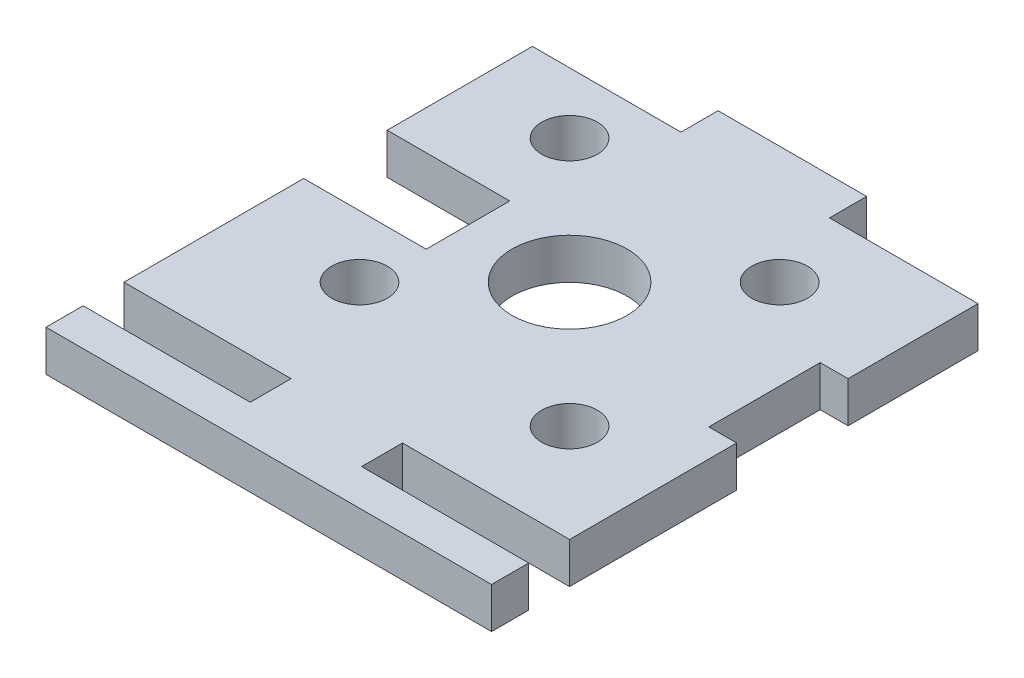
SolidWorks part; units mm, degrees
material "cardboard"
ref_plane "Front Plane" through (0, 0, 0) normal (0, 0, 1) x (1, 0, 0)
ref_plane "Top Plane" through (0, 0, 0) normal (0, 1, 0) x (1, 0, 0)
ref_plane "Right Plane" through (0, 0, 0) normal (1, 0, 0) x (0, 0, -1)
sketch "Sketch1" plane through (0, 0, 0) normal (0, 1, 0) x (1, 0, 0)
  line L0 (78.5546, 12.1341) -> (71.7044, 8.1792)
  line L1 (104.0546, -11.8659) -> (110.9047, -7.911)
  line L2 (119.2044, 8.1792) -> (110.9047, 8.1792)
  line L3 (119.2044, -7.911) -> (110.9047, -7.911)
  line L4 (71.7044, 8.1792) -> (63.4047, 8.1792)
  line L5 (126.0546, 12.1341) -> (119.2044, 8.1792)
  line L6 (126.0546, -11.8659) -> (119.2044, -7.911)
  line L7 (104.0546, 12.1341) -> (110.9047, 8.1792)
  line L8 (126.0546, 12.1341) -> (138.8046, 12.1341)
  line L9 (126.0546, -11.8659) -> (162.8046, -11.8659)
  line L10 (56.5546, 12.1341) -> (63.4047, 8.1792)
  line L11 (56.5546, -11.8659) -> (63.4047, -7.911)
  line L12 (78.5546, -11.8659) -> (71.7044, -7.911)
  line L13 (71.7044, -7.911) -> (63.4047, -7.911)
  line L14 (78.5546, 12.1341) -> (104.0546, 12.1341)
  line L15 (78.5546, -11.8659) -> (104.0546, -11.8659)
  line L16 (-11.1954, 77.8841) -> (-7.2405, 71.034)
  line L17 (12.8046, 103.3841) -> (8.8496, 110.2342)
  line L18 (-7.2405, 118.534) -> (-7.2405, 110.2342)
  line L19 (8.8496, 118.534) -> (8.8496, 110.2342)
  line L20 (-7.2405, 71.034) -> (-7.2405, 62.7342)
  line L21 (-11.1954, 125.3841) -> (-7.2405, 118.534)
  line L22 (12.8046, 125.3841) -> (8.8496, 118.534)
  line L23 (-11.1954, 103.3841) -> (-7.2405, 110.2342)
  line L24 (-11.1954, 125.3841) -> (-11.1954, 138.1341)
  line L25 (12.8046, 125.3841) -> (12.8046, 162.1341)
  line L26 (-11.1954, 55.8841) -> (-7.2405, 62.7342)
  line L27 (12.8046, 55.8841) -> (8.8496, 62.7342)
  line L28 (12.8046, 77.8841) -> (8.8496, 71.034)
  line L29 (8.8496, 71.034) -> (8.8496, 62.7342)
  line L30 (-11.1954, 77.8841) -> (-11.1954, 103.3841)
  line L31 (12.8046, 77.8841) -> (12.8046, 103.3841)
  line L32 (91.3046, 37.1341) -> (91.3046, 17.1341)
  line L33 (90.3046, 37.1341) -> (90.3046, 31.1341)
  line L34 (37.8046, 12.1341) -> (43.8046, 12.1341)
  line L35 (90.3046, 31.1341) -> (92.3046, 31.1341)
  line L36 (42.5546, 12.1341) -> (42.5546, 10.1341)
  line L37 (43.8046, 12.1341) -> (56.5546, 12.1341)
  line L38 (138.8046, 12.1341) -> (138.8046, -11.8659)
  line L39 (138.8046, 12.1341) -> (162.8046, 12.1341)
  line L40 (162.8046, 12.1341) -> (162.8046, 10.1341)
  line L41 (-27.6918, 14.4884) -> (0.8046, -14.008)
  line L42 (-27.6918, 14.4884) -> (-13.5497, 28.6305)
  line L43 (0.8046, -14.008) -> (14.9467, 0.1341)
  line L44 (-13.5497, 28.6305) -> (14.9467, 0.1341)
  line L45 (138.8046, 12.1341) -> (138.8046, 37.1341)
  line L46 (40.8046, 37.1341) -> (162.8046, 37.1341)
  line L47 (162.8046, 37.1341) -> (162.8046, 12.1341)
  line L48 (92.3046, 31.1341) -> (92.3046, 23.1341)
  line L49 (138.8046, 37.1341) -> (138.8046, 61.1341)
  line L50 (138.8046, 61.1341) -> (147.8046, 61.1341)
  line L51 (43.8046, 37.1341) -> (43.8046, 17.1341)
  line L52 (162.8046, 61.1341) -> (162.8046, 51.4561)
  line L53 (147.8046, 61.1341) -> (147.8046, 63.3341)
  line L54 (153.8046, 63.3341) -> (153.8046, 61.1341)
  line L55 (153.8046, 61.1341) -> (162.8046, 61.1341)
  line L56 (-58.1954, 138.1341) -> (-58.1954, 113.6341)
  line L57 (-38.1954, 113.6341) -> (-38.1954, 138.1341)
  line L58 (92.3046, 23.1341) -> (90.3046, 23.1341)
  line L59 (138.8046, -11.8659) -> (138.8046, -36.8659)
  line L60 (147.8046, -36.8659) -> (153.8046, -36.8659)
  line L61 (162.8046, -36.8659) -> (162.8046, -11.8659)
  line L62 (43.8046, -36.8659) -> (43.8046, -16.8659)
  line L63 (138.8046, -36.8659) -> (138.8046, -38.0459)
  line L64 (153.8046, -38.0459) -> (162.8046, -38.0459)
  line L65 (162.8046, -38.0459) -> (162.8046, -36.8659)
  line L66 (147.8046, -38.0459) -> (147.8046, -36.8659)
  line L67 (153.8046, -38.0459) -> (153.8046, -36.8659)
  line L68 (-37.3754, -137.8659) -> (-37.3754, -146.8659)
  line L69 (90.3046, 23.1341) -> (90.3046, 17.1341)
  line L70 (90.3046, 12.1341) -> (90.3046, 4.1341)
  line L71 (43.8046, -11.8659) -> (56.5546, -11.8659)
  line L72 (37.8046, -11.8659) -> (43.8046, -11.8659)
  line L73 (91.2784, 12.1341) -> (91.2784, -11.8659)
  line L74 (90.3046, 4.1341) -> (92.3046, 4.1341)
  line L75 (92.3046, 4.1341) -> (92.3046, -3.8659)
  line L76 (92.3046, -3.8659) -> (90.3046, -3.8659)
  line L77 (136.8046, 12.1341) -> (136.8046, 4.1341)
  line L78 (136.8046, 4.1341) -> (140.8046, 4.1341)
  line L79 (38.9846, 162.1341) -> (38.9846, 153.1341)
  line L80 (38.8046, 35.1341) -> (38.8046, 19.1341)
  line L81 (40.8046, 17.1341) -> (138.8046, 17.1341)
  line L82 (42.5546, 24.1341) -> (42.5546, 17.1341)
  line L83 (43.8046, 30.1341) -> (40.8046, 30.1341)
  line L84 (40.8046, 30.1341) -> (40.8046, 24.1341)
  line L85 (45.0546, 6.1341) -> (42.5546, 6.1341)
  line L86 (6.8046, -41.6159) -> (6.8046, -39.6159)
  line L87 (42.5546, -5.8659) -> (45.0546, -5.8659)
  line L88 (45.0546, 6.1341) -> (45.0546, -5.8659)
  line L89 (43.8046, 12.1341) -> (43.8046, 6.1341)
  line L90 (42.5546, 10.1341) -> (45.0546, 10.1341)
  line L91 (45.0546, 10.1341) -> (45.0546, 8.1341)
  line L92 (45.0546, 8.1341) -> (42.5546, 8.1341)
  line L93 (42.5546, 8.1341) -> (42.5546, 6.1341)
  line L94 (42.5546, -7.8659) -> (42.5546, -5.8659)
  line L95 (45.0546, -7.8659) -> (42.5546, -7.8659)
  line L96 (45.0546, -9.8659) -> (45.0546, -7.8659)
  line L97 (42.5546, -9.8659) -> (45.0546, -9.8659)
  line L98 (42.5546, -11.8659) -> (42.5546, -9.8659)
  line L99 (140.8046, 4.1341) -> (140.8046, -3.8659)
  line L100 (140.8046, -3.8659) -> (136.8046, -3.8659)
  line L101 (136.8046, -3.8659) -> (136.8046, -11.8659)
  line L102 (138.8046, 14.1341) -> (146.8046, 14.1341)
  line L103 (146.8046, 14.1341) -> (146.8046, 10.1341)
  line L104 (146.8046, 10.1341) -> (154.8046, 10.1341)
  line L105 (154.8046, 10.1341) -> (154.8046, 14.1341)
  line L106 (154.8046, 14.1341) -> (162.8046, 14.1341)
  line L107 (137.3046, 37.1341) -> (137.3046, 31.1341)
  line L108 (137.3046, 31.1341) -> (140.3046, 31.1341)
  line L109 (140.3046, 31.1341) -> (140.3046, 23.1341)
  line L110 (140.3046, 23.1341) -> (137.3046, 23.1341)
  line L111 (137.3046, 23.1341) -> (137.3046, 17.1341)
  line L112 (90.3046, -3.8659) -> (90.3046, -11.8659)
  line L113 (90.3046, -22.8659) -> (90.3046, -16.8659)
  line L114 (91.3046, -36.8659) -> (91.3046, -16.8659)
  line L115 (92.3046, -22.8659) -> (90.3046, -22.8659)
  line L116 (92.3046, -30.8659) -> (92.3046, -22.8659)
  line L117 (154.8046, -13.8659) -> (162.8046, -13.8659)
  line L118 (154.8046, -9.8659) -> (154.8046, -13.8659)
  line L119 (146.8046, -9.8659) -> (154.8046, -9.8659)
  line L120 (146.8046, -13.8659) -> (146.8046, -9.8659)
  line L121 (138.8046, -13.8659) -> (146.8046, -13.8659)
  line L122 (137.3046, -22.8659) -> (137.3046, -16.8659)
  line L123 (140.3046, -22.8659) -> (137.3046, -22.8659)
  line L124 (42.5546, 37.1341) -> (42.5546, 30.1341)
  line L125 (43.8046, 24.1341) -> (40.8046, 24.1341)
  line L126 (138.8046, -36.8659) -> (40.8046, -36.8659)
  line L127 (38.8046, -34.8659) -> (38.8046, -18.8659)
  line L128 (40.8046, -16.8659) -> (138.8046, -16.8659)
  line L129 (140.3046, -30.8659) -> (140.3046, -22.8659)
  line L130 (137.3046, -30.8659) -> (140.3046, -30.8659)
  line L131 (137.3046, -36.8659) -> (137.3046, -30.8659)
  line L132 (90.3046, -30.8659) -> (92.3046, -30.8659)
  line L133 (90.3046, -36.8659) -> (90.3046, -30.8659)
  line L134 (138.8046, 39.1341) -> (146.8046, 39.1341)
  line L135 (146.8046, 39.1341) -> (146.8046, 35.1341)
  line L136 (146.8046, 35.1341) -> (154.8046, 35.1341)
  line L137 (154.8046, 35.1341) -> (154.8046, 39.1341)
  line L138 (154.8046, 39.1341) -> (162.8046, 39.1341)
  line L139 (-43.6954, 133.8841) -> (-43.6954, 117.8841)
  line L140 (-55.1954, 133.8841) -> (-52.6954, 133.8841)
  line L141 (-55.1954, 133.8841) -> (-55.1954, 117.8841)
  line L142 (-55.1954, 117.8841) -> (-52.6954, 117.8841)
  line L143 (-52.6954, 133.8841) -> (-52.6954, 117.8841)
  line L144 (42.5546, -23.8659) -> (42.5546, -16.8659)
  line L145 (43.8046, -23.8659) -> (40.8046, -23.8659)
  line L146 (40.8046, -29.8659) -> (40.8046, -23.8659)
  line L147 (43.8046, -29.8659) -> (40.8046, -29.8659)
  line L148 (42.5546, -36.8659) -> (42.5546, -29.8659)
  line L149 (197.8046, 5.1341) -> (197.8046, -4.8659)
  line L150 (192.8046, 10.1341) -> (162.8046, 10.1341)
  line L151 (192.8046, -9.8659) -> (162.8046, -9.8659)
  line L152 (192.8046, 10.1341) -> (197.8046, 5.1341)
  line L153 (197.8046, -4.8659) -> (192.8046, -9.8659)
  line L154 (162.8046, -9.8659) -> (162.8046, -11.8659)
  line L155 (138.8046, 63.3341) -> (147.8046, 63.3341)
  line L156 (138.8046, 63.3341) -> (138.8046, 65.3341)
  line L157 (138.8046, 65.3341) -> (162.8046, 65.3341)
  line L158 (162.8046, 65.3341) -> (162.8046, 63.3341)
  line L159 (153.8046, 63.3341) -> (162.8046, 63.3341)
  line L160 (-41.1954, 117.8841) -> (-43.6954, 117.8841)
  line L161 (-41.1954, 133.8841) -> (-41.1954, 117.8841)
  line L162 (-41.1954, 133.8841) -> (-43.6954, 133.8841)
  line L163 (156.2046, 51.4561) -> (162.8046, 51.4561)
  line L164 (156.2046, 51.4561) -> (156.2046, 46.9561)
  line L165 (156.2046, 46.9561) -> (162.8046, 46.9561)
  line L166 (162.8046, 46.9561) -> (162.8046, 37.1341)
  line L167 (12.8046, -77.6159) -> (8.8496, -70.7658)
  line L168 (-11.1954, -103.1159) -> (-7.2405, -109.966)
  line L169 (8.8496, -118.2658) -> (8.8496, -109.966)
  line L170 (12.8046, -36.8659) -> (12.8046, -42.8659)
  line L171 (12.8046, -41.6159) -> (10.8046, -41.6159)
  line L172 (12.8046, -42.8659) -> (12.8046, -55.6159)
  line L173 (-7.2405, -118.2658) -> (-7.2405, -109.966)
  line L174 (8.8496, -70.7658) -> (8.8496, -62.466)
  line L175 (12.8046, -125.1159) -> (8.8496, -118.2658)
  line L176 (-11.1954, -125.1159) -> (-7.2405, -118.2658)
  line L177 (12.8046, -103.1159) -> (8.8496, -109.966)
  line L178 (12.8046, -125.1159) -> (12.8046, -137.8659)
  line L179 (-11.1954, -125.1159) -> (-11.1954, -161.8659)
  line L180 (12.8046, -55.6159) -> (8.8496, -62.466)
  line L181 (-11.1954, -55.6159) -> (-7.2405, -62.466)
  line L182 (37.8046, -42.8659) -> (17.8046, -42.8659)
  line L183 (-11.1954, -77.6159) -> (-7.2405, -70.7658)
  line L184 (-7.2405, -70.7658) -> (-7.2405, -62.466)
  line L185 (12.8046, -77.6159) -> (12.8046, -103.1159)
  line L186 (-11.1954, -77.6159) -> (-11.1954, -103.1159)
  line L187 (37.8046, -90.3659) -> (17.8046, -90.3659)
  line L188 (37.8046, -89.3659) -> (31.8046, -89.3659)
  line L189 (31.8046, -89.3659) -> (31.8046, -91.3659)
  line L190 (12.8046, -137.8659) -> (-11.1954, -137.8659)
  line L191 (12.8046, -137.8659) -> (12.8046, -161.8659)
  line L192 (12.8046, -161.8659) -> (10.8046, -161.8659)
  line L193 (12.8046, -137.8659) -> (37.8046, -137.8659)
  line L194 (37.8046, -39.8659) -> (37.8046, -161.8659)
  line L195 (-36.1954, -42.8659) -> (-16.1954, -42.8659)
  line L196 (37.8046, -161.8659) -> (12.8046, -161.8659)
  line L197 (31.8046, -91.3659) -> (23.8046, -91.3659)
  line L198 (37.8046, -137.8659) -> (61.8046, -137.8659)
  line L199 (61.8046, -137.8659) -> (61.8046, -146.8659)
  line L200 (61.8046, -161.8659) -> (52.1265, -161.8659)
  line L201 (61.8046, -146.8659) -> (64.0046, -146.8659)
  line L202 (64.0046, -152.8659) -> (61.8046, -152.8659)
  line L203 (61.8046, -152.8659) -> (61.8046, -161.8659)
  line L204 (-11.1954, -42.8659) -> (-11.1954, -55.6159)
  line L205 (-11.1954, -36.8659) -> (-11.1954, -42.8659)
  line L206 (23.8046, -91.3659) -> (23.8046, -89.3659)
  line L207 (-11.1954, -137.8659) -> (-36.1954, -137.8659)
  line L208 (-36.1954, -146.8659) -> (-36.1954, -152.8659)
  line L209 (38.9846, 147.1341) -> (38.9846, 138.1341)
  line L210 (35.8046, -37.8659) -> (19.8046, -37.8659)
  line L211 (17.8046, -39.8659) -> (17.8046, -137.8659)
  line L212 (24.8046, -41.6159) -> (17.8046, -41.6159)
  line L213 (30.8046, -42.8659) -> (30.8046, -39.8659)
  line L214 (30.8046, -39.8659) -> (24.8046, -39.8659)
  line L215 (6.8046, -44.1159) -> (6.8046, -41.6159)
  line L216 (-36.1954, -161.8659) -> (-11.1954, -161.8659)
  line L217 (-5.1954, -41.6159) -> (-5.1954, -44.1159)
  line L218 (6.8046, -44.1159) -> (-5.1954, -44.1159)
  line L219 (12.8046, -42.8659) -> (6.8046, -42.8659)
  line L220 (10.8046, -41.6159) -> (10.8046, -44.1159)
  line L221 (10.8046, -44.1159) -> (8.8046, -44.1159)
  line L222 (8.8046, -44.1159) -> (8.8046, -41.6159)
  line L223 (8.8046, -41.6159) -> (6.8046, -41.6159)
  line L224 (-7.1954, -41.6159) -> (-5.1954, -41.6159)
  line L225 (-7.1954, -44.1159) -> (-7.1954, -41.6159)
  line L226 (-9.1954, -44.1159) -> (-7.1954, -44.1159)
  line L227 (-9.1954, -41.6159) -> (-9.1954, -44.1159)
  line L228 (-11.1954, -41.6159) -> (-9.1954, -41.6159)
  line L229 (-36.1954, -137.8659) -> (-37.3754, -137.8659)
  line L230 (-37.3754, -152.8659) -> (-37.3754, -161.8659)
  line L231 (-37.3754, -161.8659) -> (-36.1954, -161.8659)
  line L232 (-37.3754, -146.8659) -> (-36.1954, -146.8659)
  line L233 (-37.3754, -152.8659) -> (-36.1954, -152.8659)
  line L234 (-161.1954, 38.3141) -> (-152.1954, 38.3141)
  line L235 (23.8046, -89.3659) -> (17.8046, -89.3659)
  line L236 (12.8046, -89.3659) -> (4.8046, -89.3659)
  line L237 (12.8046, -90.3397) -> (-11.1954, -90.3397)
  line L238 (4.8046, -89.3659) -> (4.8046, -91.3659)
  line L239 (4.8046, -91.3659) -> (-3.1954, -91.3659)
  line L240 (-3.1954, -91.3659) -> (-3.1954, -89.3659)
  line L241 (12.8046, -135.8659) -> (4.8046, -135.8659)
  line L242 (4.8046, -135.8659) -> (4.8046, -139.8659)
  line L243 (4.8046, -139.8659) -> (-3.1954, -139.8659)
  line L244 (-3.1954, -139.8659) -> (-3.1954, -135.8659)
  line L245 (-3.1954, -135.8659) -> (-11.1954, -135.8659)
  line L246 (14.8046, -137.8659) -> (14.8046, -145.8659)
  line L247 (14.8046, -145.8659) -> (10.8046, -145.8659)
  line L248 (10.8046, -145.8659) -> (10.8046, -153.8659)
  line L249 (10.8046, -153.8659) -> (14.8046, -153.8659)
  line L250 (14.8046, -153.8659) -> (14.8046, -161.8659)
  line L251 (37.8046, -136.3659) -> (31.8046, -136.3659)
  line L252 (31.8046, -136.3659) -> (31.8046, -139.3659)
  line L253 (31.8046, -139.3659) -> (23.8046, -139.3659)
  line L254 (37.8046, -41.6159) -> (30.8046, -41.6159)
  line L255 (24.8046, -42.8659) -> (24.8046, -39.8659)
  line L256 (-36.1954, -137.8659) -> (-36.1954, -39.8659)
  line L257 (-34.1954, -37.8659) -> (-18.1954, -37.8659)
  line L258 (-16.1954, -39.8659) -> (-16.1954, -137.8659)
  line L259 (23.8046, -139.3659) -> (23.8046, -136.3659)
  line L260 (23.8046, -136.3659) -> (17.8046, -136.3659)
  line L261 (-3.1954, -89.3659) -> (-11.1954, -89.3659)
  line L262 (-22.1954, -89.3659) -> (-16.1954, -89.3659)
  line L263 (-36.1954, -90.3659) -> (-16.1954, -90.3659)
  line L264 (-22.1954, -91.3659) -> (-22.1954, -89.3659)
  line L265 (-30.1954, -91.3659) -> (-22.1954, -91.3659)
  line L266 (-13.1954, -153.8659) -> (-13.1954, -161.8659)
  line L267 (-9.1954, -153.8659) -> (-13.1954, -153.8659)
  line L268 (-9.1954, -145.8659) -> (-9.1954, -153.8659)
  line L269 (-13.1954, -145.8659) -> (-9.1954, -145.8659)
  line L270 (-13.1954, -137.8659) -> (-13.1954, -145.8659)
  line L271 (-22.1954, -136.3659) -> (-16.1954, -136.3659)
  line L272 (-22.1954, -139.3659) -> (-22.1954, -136.3659)
  line L273 (-30.1954, -139.3659) -> (-22.1954, -139.3659)
  line L274 (-23.1954, -41.6159) -> (-16.1954, -41.6159)
  line L275 (-23.1954, -42.8659) -> (-23.1954, -39.8659)
  line L276 (-29.1954, -39.8659) -> (-23.1954, -39.8659)
  line L277 (-29.1954, -42.8659) -> (-29.1954, -39.8659)
  line L278 (-36.1954, -41.6159) -> (-29.1954, -41.6159)
  line L279 (-30.1954, -136.3659) -> (-30.1954, -139.3659)
  line L280 (-36.1954, -136.3659) -> (-30.1954, -136.3659)
  line L281 (-30.1954, -89.3659) -> (-30.1954, -91.3659)
  line L282 (-36.1954, -89.3659) -> (-30.1954, -89.3659)
  line L283 (39.8046, -137.8659) -> (39.8046, -145.8659)
  line L284 (39.8046, -145.8659) -> (35.8046, -145.8659)
  line L285 (35.8046, -145.8659) -> (35.8046, -153.8659)
  line L286 (35.8046, -153.8659) -> (39.8046, -153.8659)
  line L287 (39.8046, -153.8659) -> (39.8046, -161.8659)
  line L288 (5.8046, -196.8659) -> (-4.1954, -196.8659)
  line L289 (10.8046, -191.8659) -> (10.8046, -161.8659)
  line L290 (-9.1954, -191.8659) -> (-9.1954, -161.8659)
  line L291 (10.8046, -191.8659) -> (5.8046, -196.8659)
  line L292 (-4.1954, -196.8659) -> (-9.1954, -191.8659)
  line L293 (-9.1954, -161.8659) -> (-11.1954, -161.8659)
  line L294 (64.0046, -137.8659) -> (64.0046, -146.8659)
  line L295 (64.0046, -137.8659) -> (66.0046, -137.8659)
  line L296 (66.0046, -137.8659) -> (66.0046, -161.8659)
  line L297 (66.0046, -161.8659) -> (64.0046, -161.8659)
  line L298 (64.0046, -152.8659) -> (64.0046, -161.8659)
  line L299 (-36.1954, -11.8659) -> (-42.1954, -11.8659)
  line L300 (-40.9454, -11.8659) -> (-40.9454, -9.8659)
  line L301 (-42.1954, -11.8659) -> (-54.9454, -11.8659)
  line L302 (52.1265, -155.2659) -> (52.1265, -161.8659)
  line L303 (52.1265, -155.2659) -> (47.6265, -155.2659)
  line L304 (-42.1954, -36.8659) -> (-42.1954, -16.8659)
  line L305 (47.6265, -155.2659) -> (47.6265, -161.8659)
  line L306 (47.6265, -161.8659) -> (37.8046, -161.8659)
  line L307 (-76.9454, -11.8659) -> (-70.0953, -7.911)
  line L308 (-102.4454, 12.1341) -> (-109.2956, 8.1792)
  line L309 (-117.5953, -7.911) -> (-109.2956, -7.911)
  line L310 (-117.5953, 8.1792) -> (-109.2956, 8.1792)
  line L311 (-70.0953, -7.911) -> (-61.7956, -7.911)
  line L312 (-124.4454, -11.8659) -> (-117.5953, -7.911)
  line L313 (-124.4454, 12.1341) -> (-117.5953, 8.1792)
  line L314 (-102.4454, -11.8659) -> (-109.2956, -7.911)
  line L315 (-124.4454, -11.8659) -> (-137.1954, -11.8659)
  line L316 (-42.1954, 37.1341) -> (-42.1954, 17.1341)
  line L317 (-124.4454, 12.1341) -> (-161.1954, 12.1341)
  line L318 (-54.9454, -11.8659) -> (-61.7956, -7.911)
  line L319 (-54.9454, 12.1341) -> (-61.7956, 8.1792)
  line L320 (-76.9454, 12.1341) -> (-70.0953, 8.1792)
  line L321 (-70.0953, 8.1792) -> (-61.7956, 8.1792)
  line L322 (-76.9454, -11.8659) -> (-102.4454, -11.8659)
  line L323 (-76.9454, 12.1341) -> (-102.4454, 12.1341)
  line L324 (-89.6954, -36.8659) -> (-89.6954, -16.8659)
  line L325 (-42.1954, 12.1341) -> (-54.9454, 12.1341)
  line L326 (-36.1954, 12.1341) -> (-42.1954, 12.1341)
  line L327 (-88.6954, -36.8659) -> (-88.6954, -30.8659)
  line L328 (-88.6954, -30.8659) -> (-90.6954, -30.8659)
  line L329 (-137.1954, -11.8659) -> (-137.1954, 12.1341)
  line L330 (-137.1954, -11.8659) -> (-161.1954, -11.8659)
  line L331 (-161.1954, -11.8659) -> (-161.1954, -9.8659)
  line L332 (-137.1954, -11.8659) -> (-137.1954, -36.8659)
  line L333 (138.8046, -38.0459) -> (147.8046, -38.0459)
  line L334 (-37.1954, -34.8659) -> (-37.1954, -18.8659)
  line L335 (-39.1954, -16.8659) -> (-137.1954, -16.8659)
  line L336 (-40.9454, -23.8659) -> (-40.9454, -16.8659)
  line L337 (-42.1954, -29.8659) -> (-39.1954, -29.8659)
  line L338 (-39.1954, -29.8659) -> (-39.1954, -23.8659)
  line L339 (-43.4454, -5.8659) -> (-40.9454, -5.8659)
  line L340 (-39.1954, -36.8659) -> (-161.1954, -36.8659)
  line L341 (-40.9454, 6.1341) -> (-43.4454, 6.1341)
  line L342 (-43.4454, -5.8659) -> (-43.4454, 6.1341)
  line L343 (-42.1954, -11.8659) -> (-42.1954, -5.8659)
  line L344 (-40.9454, -9.8659) -> (-43.4454, -9.8659)
  line L345 (-43.4454, -9.8659) -> (-43.4454, -7.8659)
  line L346 (-43.4454, -7.8659) -> (-40.9454, -7.8659)
  line L347 (-40.9454, -7.8659) -> (-40.9454, -5.8659)
  line L348 (-40.9454, 8.1341) -> (-40.9454, 6.1341)
  line L349 (-43.4454, 8.1341) -> (-40.9454, 8.1341)
  line L350 (-43.4454, 10.1341) -> (-43.4454, 8.1341)
  line L351 (-40.9454, 10.1341) -> (-43.4454, 10.1341)
  line L352 (-40.9454, 12.1341) -> (-40.9454, 10.1341)
  line L353 (-161.1954, -36.8659) -> (-161.1954, -11.8659)
  line L354 (-90.6954, -30.8659) -> (-90.6954, -22.8659)
  line L355 (-137.1954, -36.8659) -> (-137.1954, -60.8659)
  line L356 (-137.1954, -60.8659) -> (-146.1954, -60.8659)
  line L357 (-161.1954, -60.8659) -> (-161.1954, -51.1879)
  line L358 (-146.1954, -60.8659) -> (-146.1954, -63.0659)
  line L359 (-152.1954, -63.0659) -> (-152.1954, -60.8659)
  line L360 (-152.1954, -60.8659) -> (-161.1954, -60.8659)
  line L361 (-90.6954, -22.8659) -> (-88.6954, -22.8659)
  line L362 (-137.1954, 12.1341) -> (-137.1954, 37.1341)
  line L363 (-146.1954, 37.1341) -> (-152.1954, 37.1341)
  line L364 (-161.1954, 37.1341) -> (-161.1954, 12.1341)
  line L365 (-137.1954, 37.1341) -> (-137.1954, 38.3141)
  line L366 (-161.1954, 38.3141) -> (-161.1954, 37.1341)
  line L367 (-146.1954, 38.3141) -> (-146.1954, 37.1341)
  line L368 (-152.1954, 38.3141) -> (-152.1954, 37.1341)
  line L369 (-146.1954, 38.3141) -> (-137.1954, 38.3141)
  line L370 (-88.6954, -22.8659) -> (-88.6954, -16.8659)
  line L371 (-88.6954, -11.8659) -> (-88.6954, -3.8659)
  line L372 (-89.6692, -11.8659) -> (-89.6692, 12.1341)
  line L373 (-88.6954, -3.8659) -> (-90.6954, -3.8659)
  line L374 (-40.9454, -36.8659) -> (-40.9454, -29.8659)
  line L375 (-42.1954, -23.8659) -> (-39.1954, -23.8659)
  line L376 (-137.1954, 37.1341) -> (-39.1954, 37.1341)
  line L377 (-37.1954, 35.1341) -> (-37.1954, 19.1341)
  line L378 (-39.1954, 17.1341) -> (-137.1954, 17.1341)
  line L379 (-90.6954, -3.8659) -> (-90.6954, 4.1341)
  line L380 (-90.6954, 4.1341) -> (-88.6954, 4.1341)
  line L381 (-135.1954, -11.8659) -> (-135.1954, -3.8659)
  line L382 (-135.1954, -3.8659) -> (-139.1954, -3.8659)
  line L383 (-139.1954, -3.8659) -> (-139.1954, 4.1341)
  line L384 (-139.1954, 4.1341) -> (-135.1954, 4.1341)
  line L385 (-135.1954, 4.1341) -> (-135.1954, 12.1341)
  line L386 (-137.1954, -13.8659) -> (-145.1954, -13.8659)
  line L387 (-145.1954, -13.8659) -> (-145.1954, -9.8659)
  line L388 (-145.1954, -9.8659) -> (-153.1954, -9.8659)
  line L389 (-153.1954, -9.8659) -> (-153.1954, -13.8659)
  line L390 (-153.1954, -13.8659) -> (-161.1954, -13.8659)
  line L391 (-135.6954, -36.8659) -> (-135.6954, -30.8659)
  line L392 (-36.1954, 90.6341) -> (-16.1954, 90.6341)
  line L393 (-36.1954, 89.6341) -> (-30.1954, 89.6341)
  line L394 (-40.9454, 24.1341) -> (-40.9454, 17.1341)
  line L395 (-42.1954, 24.1341) -> (-39.1954, 24.1341)
  line L396 (-39.1954, 30.1341) -> (-39.1954, 24.1341)
  line L397 (-42.1954, 30.1341) -> (-39.1954, 30.1341)
  line L398 (-40.9454, 37.1341) -> (-40.9454, 30.1341)
  line L399 (-135.6954, -30.8659) -> (-138.6954, -30.8659)
  line L400 (-138.6954, -30.8659) -> (-138.6954, -22.8659)
  line L401 (-138.6954, -22.8659) -> (-135.6954, -22.8659)
  line L402 (-135.6954, -22.8659) -> (-135.6954, -16.8659)
  line L403 (-88.6954, 4.1341) -> (-88.6954, 12.1341)
  line L404 (-88.6954, 23.1341) -> (-88.6954, 17.1341)
  line L405 (-89.6954, 37.1341) -> (-89.6954, 17.1341)
  line L406 (-90.6954, 23.1341) -> (-88.6954, 23.1341)
  line L407 (-90.6954, 31.1341) -> (-90.6954, 23.1341)
  line L408 (-153.1954, 14.1341) -> (-161.1954, 14.1341)
  line L409 (-153.1954, 10.1341) -> (-153.1954, 14.1341)
  line L410 (-145.1954, 10.1341) -> (-153.1954, 10.1341)
  line L411 (-145.1954, 14.1341) -> (-145.1954, 10.1341)
  line L412 (-137.1954, 14.1341) -> (-145.1954, 14.1341)
  line L413 (-135.6954, 23.1341) -> (-135.6954, 17.1341)
  line L414 (-138.6954, 23.1341) -> (-135.6954, 23.1341)
  line L415 (-138.6954, 31.1341) -> (-138.6954, 23.1341)
  line L416 (-135.6954, 31.1341) -> (-138.6954, 31.1341)
  line L417 (-135.6954, 37.1341) -> (-135.6954, 31.1341)
  line L418 (-88.6954, 31.1341) -> (-90.6954, 31.1341)
  line L419 (-88.6954, 37.1341) -> (-88.6954, 31.1341)
  line L420 (-137.1954, -38.8659) -> (-145.1954, -38.8659)
  line L421 (-145.1954, -38.8659) -> (-145.1954, -34.8659)
  line L422 (-145.1954, -34.8659) -> (-153.1954, -34.8659)
  line L423 (-153.1954, -34.8659) -> (-153.1954, -38.8659)
  line L424 (-153.1954, -38.8659) -> (-161.1954, -38.8659)
  line L425 (-11.1954, 41.8841) -> (-9.1954, 41.8841)
  line L426 (-30.1954, 89.6341) -> (-30.1954, 91.6341)
  line L427 (-11.1954, 138.1341) -> (12.8046, 138.1341)
  line L428 (-11.1954, 138.1341) -> (-11.1954, 162.1341)
  line L429 (-11.1954, 162.1341) -> (-9.1954, 162.1341)
  line L430 (-11.1954, 138.1341) -> (-36.1954, 138.1341)
  line L431 (-36.1954, 138.1341) -> (-36.1954, 162.1341)
  line L432 (-36.1954, 162.1341) -> (-11.1954, 162.1341)
  line L433 (-36.1954, 138.1341) -> (-36.1954, 43.1341)
  line L434 (-36.1954, 43.1341) -> (-16.1954, 43.1341)
  line L435 (-16.1954, 43.1341) -> (-16.1954, 138.1341)
  line L436 (-30.1954, 91.6341) -> (-22.1954, 91.6341)
  line L437 (-36.1954, 138.1341) -> (-60.1954, 138.1341)
  line L438 (-60.1954, 138.1341) -> (-60.1954, 147.1341)
  line L439 (-60.1954, 162.1341) -> (-50.5174, 162.1341)
  line L440 (-60.1954, 147.1341) -> (-62.3954, 147.1341)
  line L441 (-62.3954, 153.1341) -> (-60.1954, 153.1341)
  line L442 (-60.1954, 153.1341) -> (-60.1954, 162.1341)
  line L443 (-58.1954, 113.6341) -> (-38.1954, 113.6341)
  line L444 (37.8046, 43.1341) -> (17.8046, 43.1341)
  line L445 (-22.1954, 91.6341) -> (-22.1954, 89.6341)
  line L446 (37.8046, 138.1341) -> (37.8046, 43.1341)
  line L447 (17.8046, 43.1341) -> (17.8046, 138.1341)
  line L448 (12.8046, 138.1341) -> (37.8046, 138.1341)
  line L449 (37.8046, 147.1341) -> (37.8046, 153.1341)
  line L450 (37.8046, 162.1341) -> (12.8046, 162.1341)
  line L451 (12.8046, 37.1341) -> (12.8046, 55.8841)
  line L452 (37.8046, 138.1341) -> (38.9846, 138.1341)
  line L453 (38.9846, 162.1341) -> (37.8046, 162.1341)
  line L454 (38.9846, 147.1341) -> (37.8046, 147.1341)
  line L455 (38.9846, 153.1341) -> (37.8046, 153.1341)
  line L456 (-36.1954, 43.1341) -> (-36.1954, 40.1341)
  line L457 (-34.1954, 38.1341) -> (-18.1954, 38.1341)
  line L458 (-16.1954, 40.1341) -> (-16.1954, 43.1341)
  line L459 (35.8046, 38.1341) -> (19.8046, 38.1341)
  line L460 (17.8046, 40.1341) -> (17.8046, 43.1341)
  line L461 (-5.1954, 44.3841) -> (-5.1954, 41.8841)
  line L462 (-22.1954, 89.6341) -> (-16.1954, 89.6341)
  line L463 (6.8046, 41.8841) -> (6.8046, 44.3841)
  line L464 (-5.1954, 44.3841) -> (6.8046, 44.3841)
  line L465 (-11.1954, 43.1341) -> (-5.1954, 43.1341)
  line L466 (-9.1954, 41.8841) -> (-9.1954, 44.3841)
  line L467 (-9.1954, 44.3841) -> (-7.1954, 44.3841)
  line L468 (-7.1954, 44.3841) -> (-7.1954, 41.8841)
  line L469 (-7.1954, 41.8841) -> (-5.1954, 41.8841)
  line L470 (8.8046, 41.8841) -> (6.8046, 41.8841)
  line L471 (8.8046, 44.3841) -> (8.8046, 41.8841)
  line L472 (10.8046, 44.3841) -> (8.8046, 44.3841)
  line L473 (10.8046, 41.8841) -> (10.8046, 44.3841)
  line L474 (12.8046, 41.8841) -> (10.8046, 41.8841)
  line L475 (-11.1954, 89.6341) -> (-3.1954, 89.6341)
  line L476 (-11.1954, 90.6079) -> (12.8046, 90.6079)
  line L477 (-3.1954, 89.6341) -> (-3.1954, 91.6341)
  line L478 (-3.1954, 91.6341) -> (4.8046, 91.6341)
  line L479 (4.8046, 91.6341) -> (4.8046, 89.6341)
  line L480 (-11.1954, 136.1341) -> (-3.1954, 136.1341)
  line L481 (-3.1954, 136.1341) -> (-3.1954, 140.1341)
  line L482 (-3.1954, 140.1341) -> (4.8046, 140.1341)
  line L483 (4.8046, 140.1341) -> (4.8046, 136.1341)
  line L484 (4.8046, 136.1341) -> (12.8046, 136.1341)
  line L485 (-13.1954, 138.1341) -> (-13.1954, 146.1341)
  line L486 (-13.1954, 146.1341) -> (-9.1954, 146.1341)
  line L487 (-9.1954, 146.1341) -> (-9.1954, 154.1341)
  line L488 (-9.1954, 154.1341) -> (-13.1954, 154.1341)
  line L489 (-13.1954, 154.1341) -> (-13.1954, 162.1341)
  line L490 (-36.1954, 136.6341) -> (-30.1954, 136.6341)
  line L491 (-30.1954, 136.6341) -> (-30.1954, 139.6341)
  line L492 (-30.1954, 139.6341) -> (-22.1954, 139.6341)
  line L493 (-22.1954, 139.6341) -> (-22.1954, 136.6341)
  line L494 (-22.1954, 136.6341) -> (-16.1954, 136.6341)
  line L495 (4.8046, 89.6341) -> (12.8046, 89.6341)
  line L496 (23.8046, 89.6341) -> (17.8046, 89.6341)
  line L497 (37.8046, 90.6341) -> (17.8046, 90.6341)
  line L498 (23.8046, 91.6341) -> (23.8046, 89.6341)
  line L499 (31.8046, 91.6341) -> (23.8046, 91.6341)
  line L500 (-36.1954, 41.8841) -> (-29.1954, 41.8841)
  line L501 (30.8046, 40.1341) -> (24.8046, 40.1341)
  line L502 (24.8046, 41.8841) -> (17.8046, 41.8841)
  line L503 (-29.1954, 43.1341) -> (-29.1954, 40.1341)
  line L504 (-23.1954, 41.8841) -> (-16.1954, 41.8841)
  line L505 (14.8046, 154.1341) -> (14.8046, 162.1341)
  line L506 (10.8046, 154.1341) -> (14.8046, 154.1341)
  line L507 (10.8046, 146.1341) -> (10.8046, 154.1341)
  line L508 (14.8046, 146.1341) -> (10.8046, 146.1341)
  line L509 (14.8046, 138.1341) -> (14.8046, 146.1341)
  line L510 (23.8046, 136.6341) -> (17.8046, 136.6341)
  line L511 (23.8046, 139.6341) -> (23.8046, 136.6341)
  line L512 (31.8046, 139.6341) -> (23.8046, 139.6341)
  line L513 (31.8046, 136.6341) -> (31.8046, 139.6341)
  line L514 (37.8046, 136.6341) -> (31.8046, 136.6341)
  line L515 (31.8046, 89.6341) -> (31.8046, 91.6341)
  line L516 (37.8046, 89.6341) -> (31.8046, 89.6341)
  line L517 (12.8046, 37.1341) -> (21.769, 28.1696)
  line L518 (37.8046, -11.8659) -> (28.8401, -20.8304)
  line L519 (-11.1954, -36.8659) -> (-20.1599, -27.9014)
  line L520 (24.8046, 43.1341) -> (24.8046, 40.1341)
  line L521 (-23.1954, 43.1341) -> (-23.1954, 40.1341)
  line L522 (30.8046, 43.1341) -> (30.8046, 40.1341)
  line L523 (37.8046, 41.8841) -> (30.8046, 41.8841)
  line L524 (-38.1954, 138.1341) -> (-38.1954, 146.1341)
  line L525 (-38.1954, 146.1341) -> (-34.1954, 146.1341)
  line L526 (-34.1954, 146.1341) -> (-34.1954, 154.1341)
  line L527 (-34.1954, 154.1341) -> (-38.1954, 154.1341)
  line L528 (-38.1954, 154.1341) -> (-38.1954, 162.1341)
  line L529 (-58.1954, 136.6341) -> (-51.1954, 136.6341)
  line L530 (-51.1954, 136.6341) -> (-51.1954, 139.6341)
  line L531 (-51.1954, 139.6341) -> (-45.1954, 139.6341)
  line L532 (-45.1954, 139.6341) -> (-45.1954, 136.6341)
  line L533 (-45.1954, 136.6341) -> (-38.1954, 136.6341)
  line L534 (-11.1954, 37.1341) -> (-11.1954, 55.8841)
  line L535 (43.8046, -5.8659) -> (43.8046, -11.8659)
  line L536 (6.8046, 43.1341) -> (12.8046, 43.1341)
  line L537 (-42.1954, 6.1341) -> (-42.1954, 12.1341)
  line L538 (-5.1954, -42.8659) -> (-11.1954, -42.8659)
  line L539 (-4.1954, 197.1341) -> (5.8046, 197.1341)
  line L540 (-9.1954, 192.1341) -> (-9.1954, 162.1341)
  line L541 (10.8046, 192.1341) -> (10.8046, 162.1341)
  line L542 (-9.1954, 192.1341) -> (-4.1954, 197.1341)
  line L543 (5.8046, 197.1341) -> (10.8046, 192.1341)
  line L544 (134.5546, 56.1341) -> (118.5546, 56.1341)
  line L545 (134.5546, 56.1341) -> (134.5546, 53.6341)
  line L546 (-196.1954, -4.8659) -> (-196.1954, 5.1341)
  line L547 (-191.1954, -9.8659) -> (-161.1954, -9.8659)
  line L548 (-191.1954, 10.1341) -> (-161.1954, 10.1341)
  line L549 (-191.1954, -9.8659) -> (-196.1954, -4.8659)
  line L550 (-196.1954, 5.1341) -> (-191.1954, 10.1341)
  line L551 (-161.1954, 10.1341) -> (-161.1954, 12.1341)
  line L552 (-137.1954, -63.0659) -> (-146.1954, -63.0659)
  line L553 (-137.1954, -63.0659) -> (-137.1954, -65.0659)
  line L554 (-137.1954, -65.0659) -> (-161.1954, -65.0659)
  line L555 (-161.1954, -65.0659) -> (-161.1954, -63.0659)
  line L556 (10.8046, 162.1341) -> (12.8046, 162.1341)
  line L557 (-152.1954, -63.0659) -> (-161.1954, -63.0659)
  line L558 (134.5546, 53.6341) -> (118.5546, 53.6341)
  line L559 (118.5546, 56.1341) -> (118.5546, 53.6341)
  line L560 (134.5546, 44.6341) -> (118.5546, 44.6341)
  line L561 (134.5546, 42.1341) -> (134.5546, 44.6341)
  line L562 (134.5546, 42.1341) -> (118.5546, 42.1341)
  line L563 (118.5546, 42.1341) -> (118.5546, 44.6341)
  line L564 (137.3046, 59.1341) -> (137.3046, 52.1341)
  line L565 (137.3046, 52.1341) -> (140.3046, 52.1341)
  line L566 (-154.5954, -51.1879) -> (-161.1954, -51.1879)
  line L567 (-154.5954, -51.1879) -> (-154.5954, -46.6879)
  line L568 (-154.5954, -46.6879) -> (-161.1954, -46.6879)
  line L569 (-62.3954, 138.1341) -> (-62.3954, 147.1341)
  line L570 (-62.3954, 138.1341) -> (-64.3954, 138.1341)
  line L571 (-64.3954, 138.1341) -> (-64.3954, 162.1341)
  line L572 (-64.3954, 162.1341) -> (-62.3954, 162.1341)
  line L573 (-62.3954, 153.1341) -> (-62.3954, 162.1341)
  line L574 (-161.1954, -46.6879) -> (-161.1954, -36.8659)
  line L575 (140.3046, 52.1341) -> (140.3046, 46.1341)
  line L576 (-45.5575, 123.9789) -> (-46.6954, 123.9789)
  line L577 (-50.8334, 128.0202) -> (-49.6954, 128.0202)
  line L578 (-50.8334, 128.0202) -> (-50.8334, 123.9789)
  line L579 (-50.8334, 123.9789) -> (-49.6954, 123.9789)
  line L580 (-49.6954, 128.0202) -> (-49.6954, 123.9789)
  line L581 (-46.6954, 128.0202) -> (-46.6954, 123.9789)
  line L582 (-45.5575, 128.0202) -> (-46.6954, 128.0202)
  line L583 (-45.5575, 128.0202) -> (-45.5575, 123.9789)
  line L584 (140.3046, 46.1341) -> (137.3046, 46.1341)
  line L585 (137.3046, 46.1341) -> (137.3046, 39.1341)
  line L586 (114.3046, 39.1341) -> (138.8046, 39.1341)
  line L587 (114.3046, 59.1341) -> (114.3046, 39.1341)
  line L588 (138.8046, 59.1341) -> (114.3046, 59.1341)
  line L589 (56.8046, -133.6159) -> (56.8046, -117.6159)
  line L590 (56.8046, -133.6159) -> (54.3046, -133.6159)
  line L591 (-50.5174, 155.5341) -> (-50.5174, 162.1341)
  line L592 (-50.5174, 155.5341) -> (-46.0174, 155.5341)
  line L593 (-46.0174, 155.5341) -> (-46.0174, 162.1341)
  line L594 (-46.0174, 162.1341) -> (-36.1954, 162.1341)
  line L595 (54.3046, -133.6159) -> (54.3046, -117.6159)
  line L596 (56.8046, -117.6159) -> (54.3046, -117.6159)
  line L597 (-13.0888, 35.2407) -> (-11.1954, 37.1341)
  line L598 (-20.1599, 35.2407) -> (-22.2812, 37.362)
  line L599 (-34.302, 21.0986) -> (-36.4233, 23.2199)
  line L600 (-36.4233, 23.2199) -> (-22.2812, 37.362)
  line L601 (6.8046, -39.6159) -> (-5.1954, -39.6159)
  line L602 (42.5546, 6.1341) -> (40.5546, 6.1341)
  line L603 (-5.1954, -41.6159) -> (-5.1954, -39.6159)
  line L604 (42.5546, -5.8659) -> (40.5546, -5.8659)
  line L605 (40.5546, 6.1341) -> (40.5546, -5.8659)
  line L606 (-40.9454, -5.8659) -> (-38.9454, -5.8659)
  line L607 (-38.9454, -5.8659) -> (-38.9454, 6.1341)
  line L608 (-40.9454, 6.1341) -> (-38.9454, 6.1341)
  line L609 (-5.1954, 41.8841) -> (-5.1954, 39.8841)
  line L610 (-5.1954, 39.8841) -> (6.8046, 39.8841)
  line L611 (6.8046, 41.8841) -> (6.8046, 39.8841)
  line L612 (-36.1954, 12.1341) -> (-34.302, 14.0275)
  line L613 (-29.1954, 40.1341) -> (-23.1954, 40.1341)
  line L614 (26.7188, -18.709) -> (19.6477, -25.7801)
  line L615 (19.6477, 26.0483) -> (26.7188, 18.9772)
  line L616 (26.7188, 18.9772) -> (28.8401, 21.0986)
  line L617 (45.3046, -133.6159) -> (45.3046, -117.6159)
  line L618 (42.8046, -133.6159) -> (45.3046, -133.6159)
  line L619 (42.8046, -133.6159) -> (42.8046, -117.6159)
  line L620 (42.8046, -117.6159) -> (45.3046, -117.6159)
  line L621 (59.8046, -136.3659) -> (52.8046, -136.3659)
  line L622 (52.8046, -136.3659) -> (52.8046, -139.3659)
  line L623 (52.8046, -139.3659) -> (46.8046, -139.3659)
  line L624 (46.8046, -139.3659) -> (46.8046, -136.3659)
  line L625 (46.8046, -136.3659) -> (39.8046, -136.3659)
  line L626 (39.8046, -113.3659) -> (39.8046, -137.8659)
  line L627 (59.8046, -113.3659) -> (39.8046, -113.3659)
  line L628 (59.8046, -137.8659) -> (59.8046, -113.3659)
  line L629 (-132.9454, -55.8659) -> (-116.9454, -55.8659)
  line L630 (-132.9454, -55.8659) -> (-132.9454, -53.3659)
  line L631 (-132.9454, -53.3659) -> (-116.9454, -53.3659)
  line L632 (-116.9454, -55.8659) -> (-116.9454, -53.3659)
  line L633 (-132.9454, -44.3659) -> (-116.9454, -44.3659)
  line L634 (-132.9454, -41.8659) -> (-132.9454, -44.3659)
  line L635 (-132.9454, -41.8659) -> (-116.9454, -41.8659)
  line L636 (-116.9454, -41.8659) -> (-116.9454, -44.3659)
  line L637 (-135.6954, -58.8659) -> (-135.6954, -51.8659)
  line L638 (-135.6954, -51.8659) -> (-138.6954, -51.8659)
  line L639 (-138.6954, -51.8659) -> (-138.6954, -45.8659)
  line L640 (-138.6954, -45.8659) -> (-135.6954, -45.8659)
  line L641 (-135.6954, -45.8659) -> (-135.6954, -38.8659)
  line L642 (-112.6954, -38.8659) -> (-137.1954, -38.8659)
  line L643 (-112.6954, -58.8659) -> (-112.6954, -38.8659)
  line L644 (-137.1954, -58.8659) -> (-112.6954, -58.8659)
  line L645 (128.6907, 51.772) -> (124.6494, 51.772)
  line L646 (128.6907, 51.772) -> (128.6907, 50.6341)
  line L647 (128.6907, 50.6341) -> (124.6494, 50.6341)
  line L648 (124.6494, 51.772) -> (124.6494, 50.6341)
  line L649 (128.6907, 47.6341) -> (124.6494, 47.6341)
  line L650 (19.6477, 26.0483) -> (21.769, 28.1696)
  line L651 (128.6907, 46.4962) -> (128.6907, 47.6341)
  line L652 (128.6907, 46.4962) -> (124.6494, 46.4962)
  line L653 (124.6494, 46.4962) -> (124.6494, 47.6341)
  line L654 (52.4425, -127.752) -> (52.4425, -123.7107)
  line L655 (52.4425, -127.752) -> (51.3046, -127.752)
  line L656 (51.3046, -127.752) -> (51.3046, -123.7107)
  line L657 (52.4425, -123.7107) -> (51.3046, -123.7107)
  line L658 (48.3046, -127.752) -> (48.3046, -123.7107)
  line L659 (47.1666, -127.752) -> (48.3046, -127.752)
  line L660 (47.1666, -127.752) -> (47.1666, -123.7107)
  line L661 (47.1666, -123.7107) -> (48.3046, -123.7107)
  line L662 (-127.0815, -51.5038) -> (-123.0402, -51.5038)
  line L663 (-127.0815, -51.5038) -> (-127.0815, -50.3659)
  line L664 (-127.0815, -50.3659) -> (-123.0402, -50.3659)
  line L665 (-123.0402, -51.5038) -> (-123.0402, -50.3659)
  line L666 (-127.0815, -47.3659) -> (-123.0402, -47.3659)
  line L667 (-127.0815, -46.228) -> (-127.0815, -47.3659)
  line L668 (-127.0815, -46.228) -> (-123.0402, -46.228)
  line L669 (-123.0402, -46.228) -> (-123.0402, -47.3659)
  line L670 (28.8401, 21.0986) -> (37.8046, 12.1341)
  line L671 (19.6477, -25.7801) -> (21.769, -27.9014)
  line L672 (26.7188, -18.709) -> (28.8401, -20.8304)
  line L673 (-18.0386, -25.7801) -> (-25.1096, -18.709)
  line L674 (-25.1096, -18.709) -> (-27.231, -20.8304)
  line L675 (-18.0386, -25.7801) -> (-20.1599, -27.9014)
  line L676 (21.769, -27.9014) -> (12.8046, -36.8659)
  line L677 (-27.231, -20.8304) -> (-36.1954, -11.8659)
  line L678 (37.8046, 43.1341) -> (37.8046, 40.1341)
  circle A0 centre (157.5221, 42.4166) radius 1.5
  circle A1 centre (144.0871, 55.8516) radius 1.5
  circle A2 centre (156.4614, 54.791) radius 1.5
  circle A3 centre (145.1477, 43.4772) radius 1.5
  circle A4 centre (150.8046, 49.1341) radius 3.1
  circle A5 centre (150.8046, 24.6341) radius 5
  circle A6 centre (150.8046, -24.3659) radius 5
  circle A7 centre (67.5546, 27.1341) radius 5
  circle A8 centre (114.8052, 27.1341) radius 5
  circle A9 centre (67.5546, -26.8659) radius 5
  circle A10 centre (114.8052, -26.8659) radius 5
  circle A11 centre (150.8046, 0.1341) radius 7
  circle A12 centre (43.0871, -156.5834) radius 1.5
  circle A13 centre (56.5221, -143.1484) radius 1.5
  circle A14 centre (55.4614, -155.5228) radius 1.5
  circle A15 centre (44.1477, -144.209) radius 1.5
  circle A16 centre (49.8046, -149.8659) radius 3.1
  circle A17 centre (25.3046, -149.8659) radius 5
  circle A18 centre (-41.4779, 156.8516) radius 1.5
  circle A19 centre (-54.9129, 143.4166) radius 1.5
  circle A20 centre (-53.8523, 155.791) radius 1.5
  circle A21 centre (-42.5386, 144.4772) radius 1.5
  circle A22 centre (-48.1954, 150.1341) radius 3.1
  circle A23 centre (-23.6954, -149.8659) radius 5
  circle A24 centre (27.8046, -66.6159) radius 5
  circle A25 centre (27.8046, -113.8665) radius 5
  circle A26 centre (-26.1954, -66.6159) radius 5
  circle A27 centre (-26.1954, -113.8665) radius 5
  circle A28 centre (0.8046, -149.8659) radius 7
  circle A29 centre (-155.9129, -42.1484) radius 1.5
  circle A30 centre (-23.6954, 150.1341) radius 5
  circle A31 centre (25.3046, 150.1341) radius 5
  circle A32 centre (-142.4779, -55.5834) radius 1.5
  circle A33 centre (-154.8523, -54.5228) radius 1.5
  circle A34 centre (-143.5386, -43.209) radius 1.5
  circle A35 centre (-149.1954, -48.8659) radius 3.1
  circle A36 centre (-149.1954, -24.3659) radius 5
  circle A37 centre (-149.1954, 24.6341) radius 5
  circle A38 centre (-65.9454, -26.8659) radius 5
  circle A39 centre (-113.196, -26.8659) radius 5
  circle A40 centre (-65.9454, 27.1341) radius 5
  circle A41 centre (-113.196, 27.1341) radius 5
  circle A42 centre (-149.1954, 0.1341) radius 7
  circle A43 centre (-26.1954, 66.8841) radius 5
  circle A44 centre (-26.1954, 114.1347) radius 5
  circle A45 centre (27.8046, 66.8841) radius 5
  circle A46 centre (27.8046, 114.1347) radius 5
  arc A47 (40.8046, 37.1341) -> (38.8046, 35.1341) centre (40.8046, 35.1341) ccw
  arc A48 (38.8046, 19.1341) -> (40.8046, 17.1341) centre (40.8046, 19.1341) ccw
  arc A49 (-18.1954, 38.1341) -> (-16.1954, 40.1341) centre (-18.1954, 40.1341) ccw
  arc A50 (-36.1954, 40.1341) -> (-34.1954, 38.1341) centre (-34.1954, 40.1341) ccw
  arc A51 (37.8046, 40.1341) -> (35.8046, 38.1341) centre (35.8046, 40.1341) cw
  arc A52 (19.8046, 38.1341) -> (17.8046, 40.1341) centre (19.8046, 40.1341) cw
  arc A53 (40.8046, -36.8659) -> (38.8046, -34.8659) centre (40.8046, -34.8659) cw
  arc A54 (38.8046, -18.8659) -> (40.8046, -16.8659) centre (40.8046, -18.8659) cw
  arc A55 (37.8046, -39.8659) -> (35.8046, -37.8659) centre (35.8046, -39.8659) ccw
  arc A56 (19.8046, -37.8659) -> (17.8046, -39.8659) centre (19.8046, -39.8659) ccw
  arc A57 (-36.1954, -39.8659) -> (-34.1954, -37.8659) centre (-34.1954, -39.8659) cw
  arc A58 (-18.1954, -37.8659) -> (-16.1954, -39.8659) centre (-18.1954, -39.8659) cw
  arc A59 (-39.1954, -36.8659) -> (-37.1954, -34.8659) centre (-39.1954, -34.8659) ccw
  arc A60 (-37.1954, -18.8659) -> (-39.1954, -16.8659) centre (-39.1954, -18.8659) ccw
  arc A61 (-39.1954, 37.1341) -> (-37.1954, 35.1341) centre (-39.1954, 35.1341) cw
  arc A62 (-37.1954, 19.1341) -> (-39.1954, 17.1341) centre (-39.1954, 19.1341) cw
  arc A63 (-13.0888, 35.2407) -> (-20.1599, 35.2407) centre (-16.6244, 38.7762) cw
  arc A64 (-34.302, 21.0986) -> (-34.302, 14.0275) centre (-37.8376, 17.563) cw
  circle A65 centre (0.8046, 150.1341) radius 7
  point P194 (0.8046, 0.1341)
  point P589 (0.8046, 0.1341)
  point P595 (0.8046, 0.1341)
  point P596 (0.8046, 0.1341)
  point P601 (0.8046, 0.1341)
  point P604 (0.8046, 0.1341)
  point P629 (0.8046, 0.1341)
  point P660 (0.8046, 0.1341)
  point P686 (0.8046, 0.1341)
  point P715 (0.8046, 0.1341)
  point P716 (0.8046, 0.1341)
  point P740 (0.8046, 0.1341)
  point P743 (0.8046, 0.1341)
  point P783 (0.8046, 0.1341)
  point P809 (0.8046, 0.1341)
  point P816 (0.8046, 0.1341)
  point P829 (0.8046, 0.1341)
  point P860 (0.8046, 0.1341)
  point P885 (0.8046, 0.1341)
  point P890 (0.8046, 0.1341)
  point P910 (0.8046, 0.1341)
extrude "Boss-Extrude1" add sketch "Sketch1" along normal blind 2.2 contours L639 L640 L355 L420 L421 L340 L423 L424 L574 L568 L567 L566 L357 L360 L359 L557 L555 L554 L553 L552 L358 L356 L638 A35 A34 A33 A32 A29
